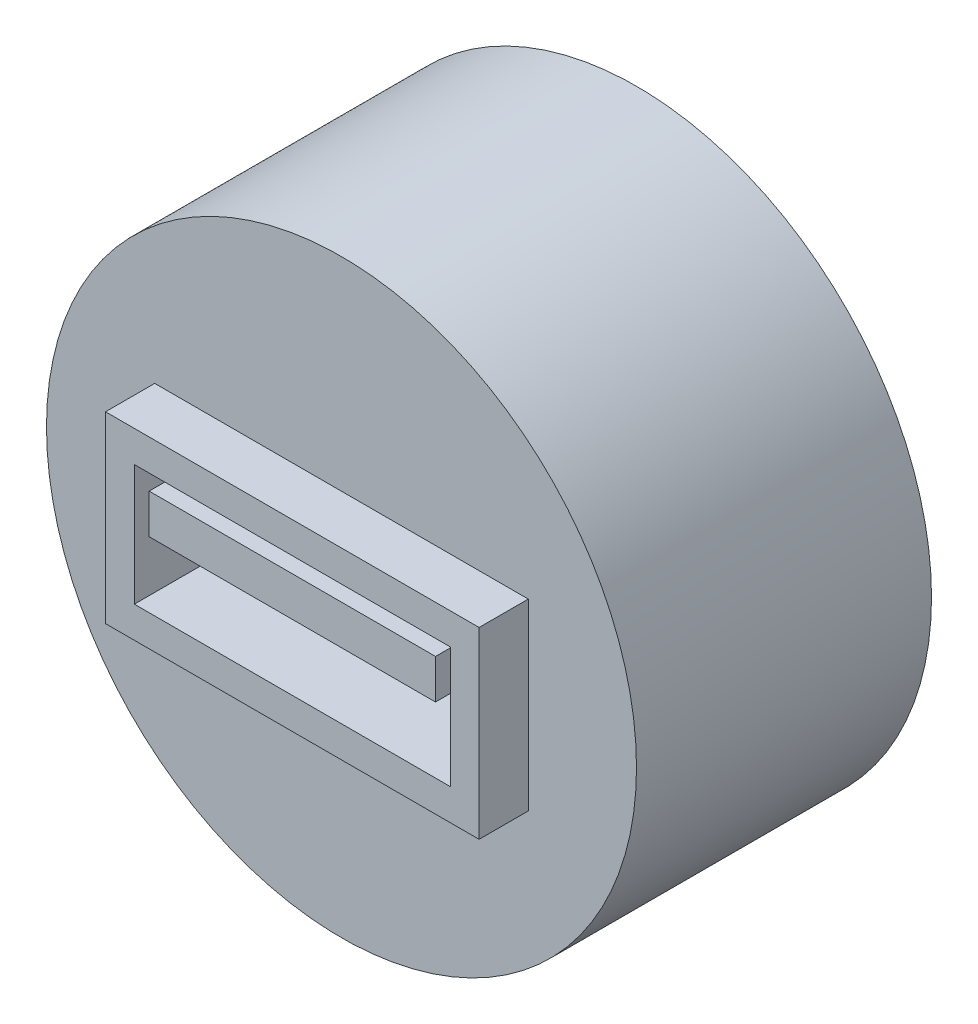
SolidWorks part; units mm, degrees
ref_plane "Front Plane" through (0, 0, 0) normal (0, 0, 1) x (1, 0, 0)
ref_plane "Top Plane" through (0, 0, 0) normal (0, 1, 0) x (1, 0, 0)
ref_plane "Right Plane" through (0, 0, 0) normal (1, 0, 0) x (0, 0, -1)
sketch "Sketch2" plane through (0, 0, 0) normal (0, 0, 1) x (1, 0, 0)
  circle A0 centre (0, 0) radius 12
  dimension "D1" = 24
extrude "Boss-Extrude1" add sketch "Sketch2" along normal blind 12
sketch "Sketch4" plane through (0, 0, 12) normal (0, 0, 1) x (1, 0, 0)
  line L1 (-7.5976, 3.7319) -> (7.5976, 3.7319)
  line L2 (-7.5976, 3.7319) -> (-7.5976, -3.7319)
  line L3 (-7.5976, -3.7319) -> (7.5976, -3.7319)
  line L4 (7.5976, 3.7319) -> (7.5976, -3.7319)
  line L5 (-7.5976, 3.7319) -> (7.5976, -3.7319) construction
  line L6 (-7.5976, -3.7319) -> (7.5976, 3.7319) construction
  line L7 (-6.4262, 2.46) -> (6.4262, 2.46)
  line L8 (-6.4262, 2.46) -> (-6.4262, -2.46)
  line L9 (-6.4262, -2.46) -> (6.4262, -2.46)
  line L10 (6.4262, 2.46) -> (6.4262, -2.46)
  line L11 (-6.4262, 2.46) -> (6.4262, -2.46) construction
  line L12 (-6.4262, -2.46) -> (6.4262, 2.46) construction
  point P0 (0, 0)
  point P6 (0, 0)
extrude "Boss-Extrude2" add sketch "Sketch4" along normal blind 2
sketch "Sketch5" plane through (0, 0, 12) normal (0, 0, 1) x (1, 0, 0)
  line L1 (-5.8237, 1.8241) -> (5.8237, 1.8241)
  line L2 (-5.8237, 1.8241) -> (-5.8237, 0.2176)
  line L3 (-5.8237, 0.2176) -> (5.8237, 0.2176)
  line L4 (5.8237, 1.8241) -> (5.8237, 0.2176)
  line L5 (-5.8237, 1.8241) -> (5.8237, 0.2176) construction
  line L6 (-5.8237, 0.2176) -> (5.8237, 1.8241) construction
  point P0 (0, 1.0208)
extrude "Boss-Extrude3" add sketch "Sketch5" along normal up to surface (2 mm away) up to face at (0, 0, 14)
sketch "Sketch6" plane through (0, 0, 12) normal (0, 0, 1) x (1, 0, 0)
  line L4 (6.4262, -2.46) -> (6.4262, 2.46)
  line L5 (6.4262, 2.46) -> (-6.4262, 2.46)
  line L6 (-6.4262, 2.46) -> (-6.4262, -2.46)
  line L7 (-6.4262, -2.46) -> (6.4262, -2.46)
  line L8 (6.4262, -2.46) -> (6.4262, 2.46)
  line L9 (6.4262, 2.46) -> (-6.4262, 2.46)
  line L10 (-6.4262, 2.46) -> (-6.4262, -2.46)
  line L11 (-6.4262, -2.46) -> (6.4262, -2.46)
  line L12 (-5.8237, 0.2176) -> (5.8237, 0.2176)
  line L13 (5.8237, 0.2176) -> (5.8237, 1.8241)
  line L14 (5.8237, 1.8241) -> (-5.8237, 1.8241)
  line L15 (-5.8237, 1.8241) -> (-5.8237, 0.2176)
  line L16 (-5.8237, 0.2176) -> (5.8237, 0.2176)
  line L17 (5.8237, 0.2176) -> (5.8237, 1.8241)
  line L18 (5.8237, 1.8241) -> (-5.8237, 1.8241)
  line L19 (-5.8237, 1.8241) -> (-5.8237, 0.2176)
  dimension "D1" = 0
  dimension "D2" = 0
extrude "Cut-Extrude1" cut sketch "Sketch6" against normal blind 2
